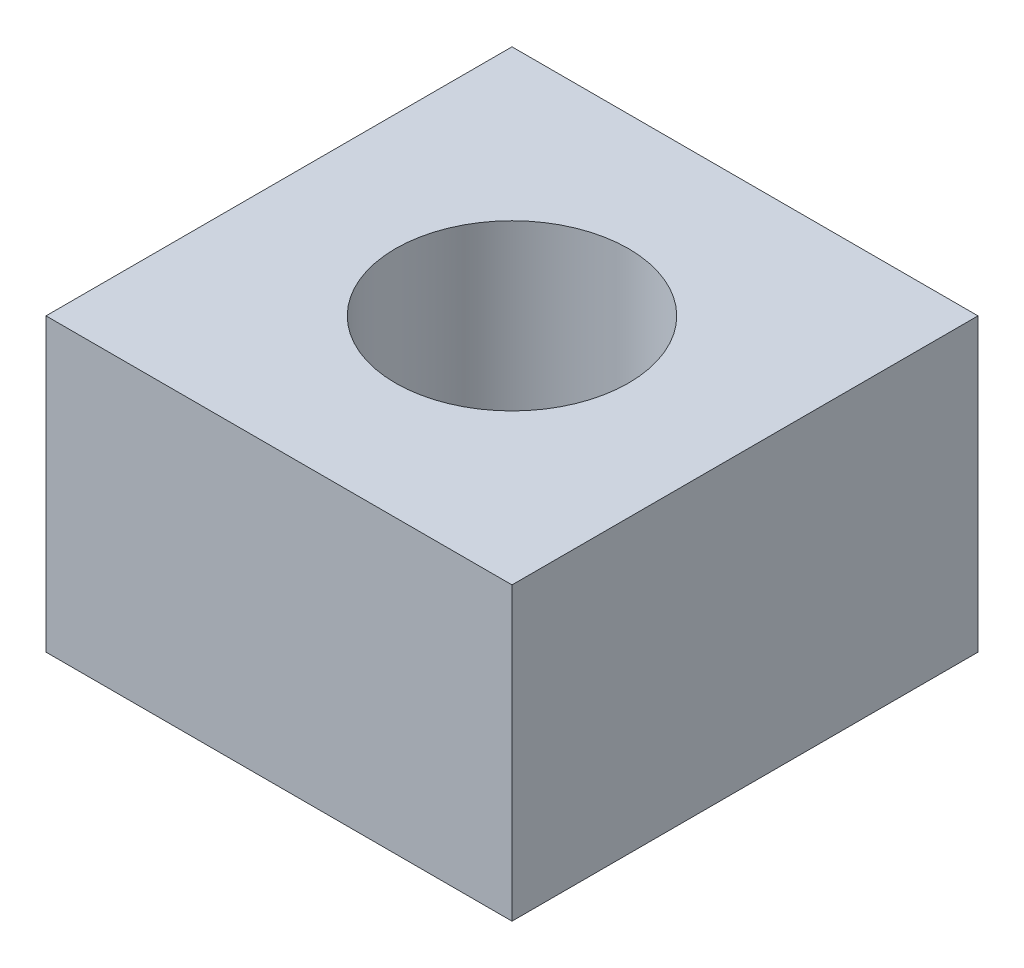
SolidWorks part; units mm, degrees
ref_plane "前视基准面" through (0, 0, 0) normal (0, 0, 1) x (1, 0, 0)
ref_plane "上视基准面" through (0, 0, 0) normal (0, 1, 0) x (1, 0, 0)
ref_plane "右视基准面" through (0, 0, 0) normal (1, 0, 0) x (0, 0, -1)
other "Configuration Table"
sketch "草图1" plane through (0, 0, 0) normal (0, 1, 0) x (1, 0, 0)
  line L0 (40, 40) -> (40, -40)
  line L1 (40, -40) -> (-40, -40)
  line L2 (-40, -40) -> (-40, 40)
  line L3 (-40, 40) -> (40, 40)
  circle A0 centre (0, 0) radius 20
extrude "凸台-拉伸1" add sketch "草图1" along normal blind 50
